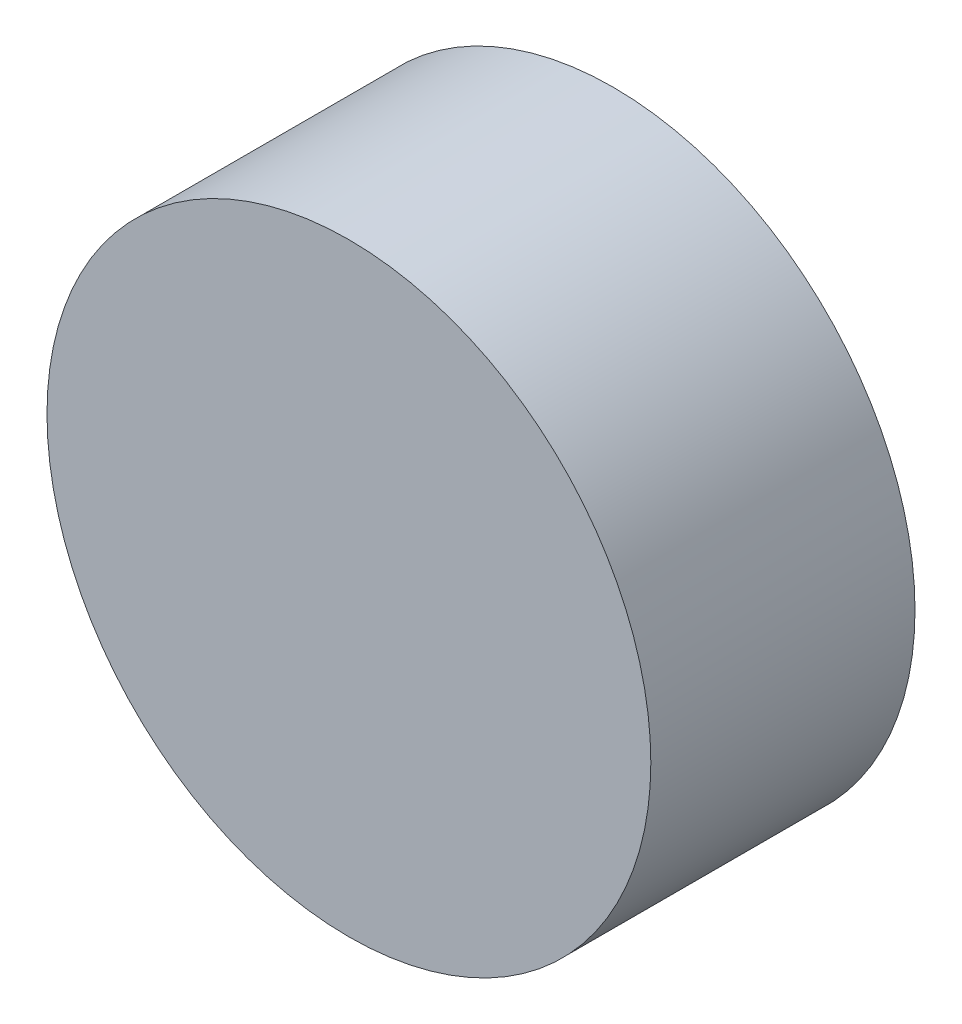
SolidWorks part; units mm, degrees
material "ABS"
ref_plane "Front Plane" through (0, 0, 0) normal (0, 0, 1) x (1, 0, 0)
ref_plane "Top Plane" through (0, 0, 0) normal (0, 1, 0) x (1, 0, 0)
ref_plane "Right Plane" through (0, 0, 0) normal (1, 0, 0) x (0, 0, -1)
sketch "Extrude sketch 1" plane through (0, 0, 0) normal (0, 0, 1) x (1, 0, 0)
  circle A0 centre (0, 0) radius 16
  dimension "D1" = 32
extrude "Extrude 1" add sketch "Extrude sketch 1" along normal blind 14 separate body
